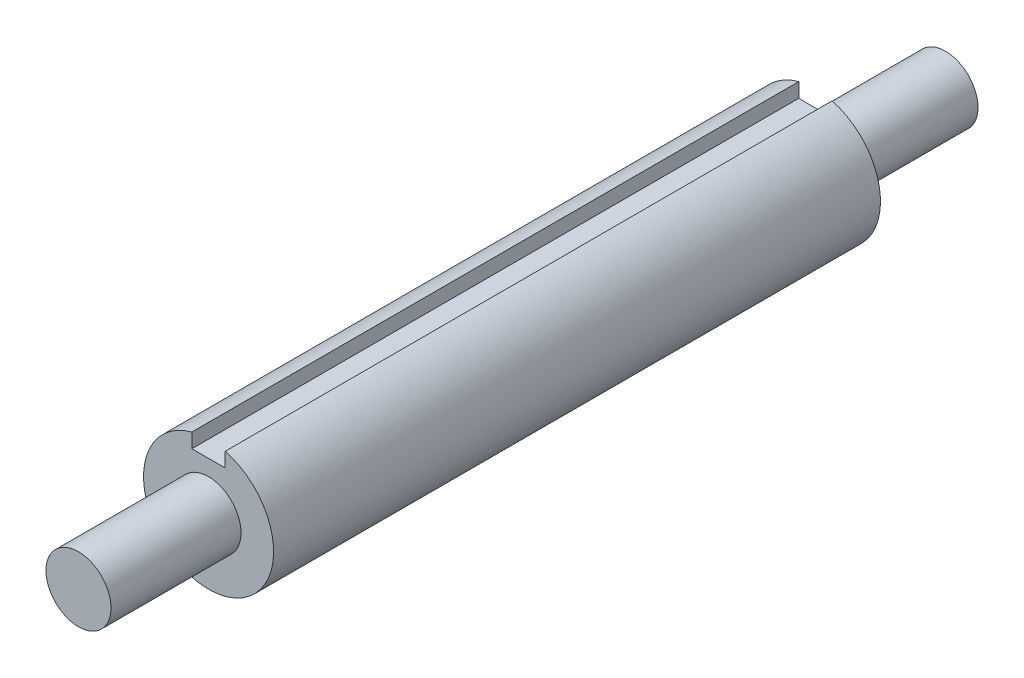
SolidWorks part; units mm, degrees
ref_plane "Front Plane" through (0, 0, 0) normal (0, 0, 1) x (1, 0, 0)
ref_plane "Top Plane" through (0, 0, 0) normal (0, 1, 0) x (1, 0, 0)
ref_plane "Right Plane" through (0, 0, 0) normal (1, 0, 0) x (0, 0, -1)
sketch "Sketch1" plane through (0, 0, 0) normal (0, 0, 1) x (1, 0, 0)
  circle A0 centre (0, 0) radius 3.75
  dimension "D1" = 7.5
extrude "Boss-Extrude1" add sketch "Sketch1" along normal blind 100
ref_plane "Plane1" through (0, 0, 50) normal (0, 0, -1) x (-1, 0, 0)
sketch "Sketch2" plane through (0, 0, 50) normal (0, 0, -1) x (-1, 0, 0)
  circle A0 centre (0, 0) radius 7.5
  dimension "D1" = 15
extrude "Boss-Extrude2" add sketch "Sketch2" along normal blind 35 and the other way blind 35
sketch "Sketch3" plane through (0, 0, 50) normal (0, 0, -1) x (-1, 0, 0)
  line L1 (-1.925, 9.425) -> (1.925, 9.425)
  line L2 (-1.925, 9.425) -> (-1.925, 5.575)
  line L3 (-1.925, 5.575) -> (1.925, 5.575)
  line L4 (1.925, 9.425) -> (1.925, 5.575)
  line L5 (-1.925, 9.425) -> (1.925, 5.575) construction
  line L6 (-1.925, 5.575) -> (1.925, 9.425) construction
  circle A0 centre (0, 0) radius 7.5 construction
  circle A1 centre (0, 0) radius 7.5 construction
  point P0 (0, 7.5)
  dimension "D1" = 3.85
  dimension "D2" = 3.85
extrude "Cut-Extrude1" cut sketch "Sketch3" against normal up to surface and the other way up to surface contours L4 L3 L2 L1 up to face at (-3.75, 0, 85) other way up to face at (-3.75, 0, 15)
